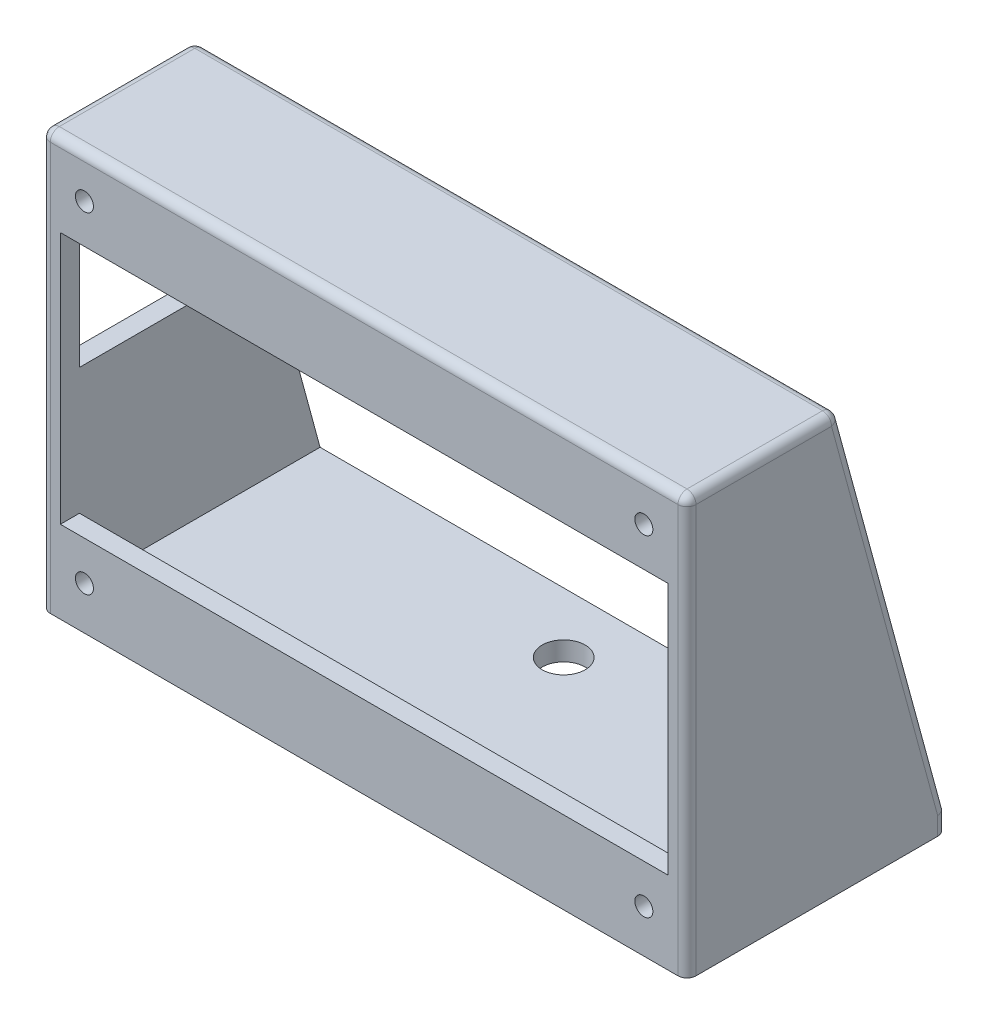
SolidWorks part; units mm, degrees
material "ABS"
ref_plane "Front Plane" through (0, 0, 0) normal (0, 0, 1) x (1, 0, 0)
ref_plane "Top Plane" through (0, 0, 0) normal (0, 1, 0) x (1, 0, 0)
ref_plane "Right Plane" through (0, 0, 0) normal (1, 0, 0) x (0, 0, -1)
sketch "Sketch1" plane through (0, 0, 0) normal (0, 0, 1) x (1, 0, 0)
  line L1 (-53.675, -34.675) -> (53.675, -34.675)
  line L2 (-53.675, -34.675) -> (-53.675, 34.675)
  line L3 (-53.675, 34.675) -> (53.675, 34.675)
  line L4 (53.675, -34.675) -> (53.675, 34.675)
  line L5 (-53.675, -34.675) -> (53.675, 34.675) construction
  line L6 (-53.675, 34.675) -> (53.675, -34.675) construction
  point P0 (0, 0)
  dimension "D1" = 107.35
  dimension "D2" = 69.35
extrude "Boss-Extrude1" add sketch "Sketch1" along normal mid plane 3.175
sketch "Sketch2" plane through (0, 0, 0) normal (0, 0, 1) x (1, 0, 0)
  line L1 (-50.5, -21) -> (50.5, -21)
  line L2 (-50.5, -21) -> (-50.5, 21)
  line L3 (-50.5, 21) -> (50.5, 21)
  line L4 (50.5, -21) -> (50.5, 21)
  line L5 (-50.5, -21) -> (50.5, 21) construction
  line L6 (-50.5, 21) -> (50.5, -21) construction
  line L7 (-46.5, -27.5) -> (46.5, -27.5) construction
  line L8 (-46.5, -27.5) -> (-46.5, 27.5) construction
  line L9 (-46.5, 27.5) -> (46.5, 27.5) construction
  line L10 (46.5, -27.5) -> (46.5, 27.5) construction
  line L11 (-46.5, -27.5) -> (46.5, 27.5) construction
  line L12 (-46.5, 27.5) -> (46.5, -27.5) construction
  circle A0 centre (-46.5, 27.5) radius 1.5
  circle A1 centre (46.5, 27.5) radius 1.5
  circle A2 centre (46.5, -27.5) radius 1.5
  circle A3 centre (-46.5, -27.5) radius 1.5
  point P0 (0, 0)
  point P6 (0, 0)
  dimension "D1" = 101
  dimension "D2" = 42
  dimension "D3" = 93
  dimension "D4" = 55
extrude "Cut-Extrude2" cut sketch "Sketch2" against normal through all both and the other way through all
sketch "Sketch3" plane through (0, 0, -1.5875) normal (0, 0, -1) x (-1, 0, 0)
  line L1 (-53.675, -34.675) -> (53.675, -34.675)
  line L2 (-53.675, -34.675) -> (-53.675, 34.675)
  line L3 (-53.675, 34.675) -> (53.675, 34.675)
  line L4 (53.675, -34.675) -> (53.675, 34.675)
  line L5 (-53.675, -34.675) -> (53.675, 34.675) construction
  line L6 (-53.675, 34.675) -> (53.675, -34.675) construction
  line L7 (-50.5, -31.5) -> (50.5, -31.5)
  line L8 (-50.5, -31.5) -> (-50.5, 31.5)
  line L9 (-50.5, 31.5) -> (50.5, 31.5)
  line L10 (50.5, -31.5) -> (50.5, 31.5)
  line L11 (-50.5, -31.5) -> (50.5, 31.5) construction
  line L12 (-50.5, 31.5) -> (50.5, -31.5) construction
  point P0 (0, 0)
  point P7 (0, 0)
  dimension "D1" = 3.175
  dimension "D2" = 3.175
extrude "Boss-Extrude2" add sketch "Sketch3" along normal blind 40
sketch "Sketch5" plane through (0, -31.5, 0) normal (0, 1, 0) x (1, 0, 0)
  line L1 (0, 1.5875) -> (0, 31.5875) construction
  line L2 (50.5, 1.5875) -> (-50.5, 1.5875) construction
  circle A0 centre (0, 31.5875) radius 3.5719
extrude "Cut-Extrude3" cut sketch "Sketch5" against normal blind 25.4
sketch "Sketch8" plane through (-53.675, 0, 0) normal (-1, 0, 0) x (0, 0, 1)
  line L0 (-41.5875, -34.675) -> (-41.5875, -31.5) construction
  line L1 (-41.5875, -34.675) -> (-41.5875, 34.675) construction
  line L2 (1.5875, 34.675) -> (-23.5875, 34.675) construction
  line L3 (1.5875, 34.675) -> (-41.5875, 34.675) construction
  line L4 (-23.5875, 34.675) -> (-41.5875, -31.5)
  line L5 (-41.5875, -31.5) -> (-41.5875, 34.675)
  line L6 (-41.5875, 34.675) -> (-23.5875, 34.675)
extrude "Cut-Extrude4" cut sketch "Sketch8" against normal through all
sketch "Sketch10" plane through (-50.5, 0, 0) normal (1, 0, 0) x (0, 0, -1)
  line L0 (1.5875, 31.5) -> (1.5875, 0)
  line L1 (1.5875, 0) -> (48.9584, 0)
  line L2 (48.9584, 0) -> (48.9584, 31.5)
  line L3 (48.9584, 31.5) -> (1.5875, 31.5)
extrude "Cut-Extrude5" cut sketch "Sketch10" against normal blind 25.4
fillet "Fillet1" radius 1.5 11 edges at (0, 34.675, -23.5875) (53.675, 1.5875, -32.5875) (53.675, 34.675, -11) (-53.675, 34.675, -11) (53.675, 0, 1.5875) (0, 34.675, 1.5875) (-53.675, 0, 1.5875) (53.675, -33.0875, -41.5875) (-53.675, -33.0875, -41.5875) (-53.675, -15.75, -37.3034) (-53.675, 33.0875, -24.0193)
